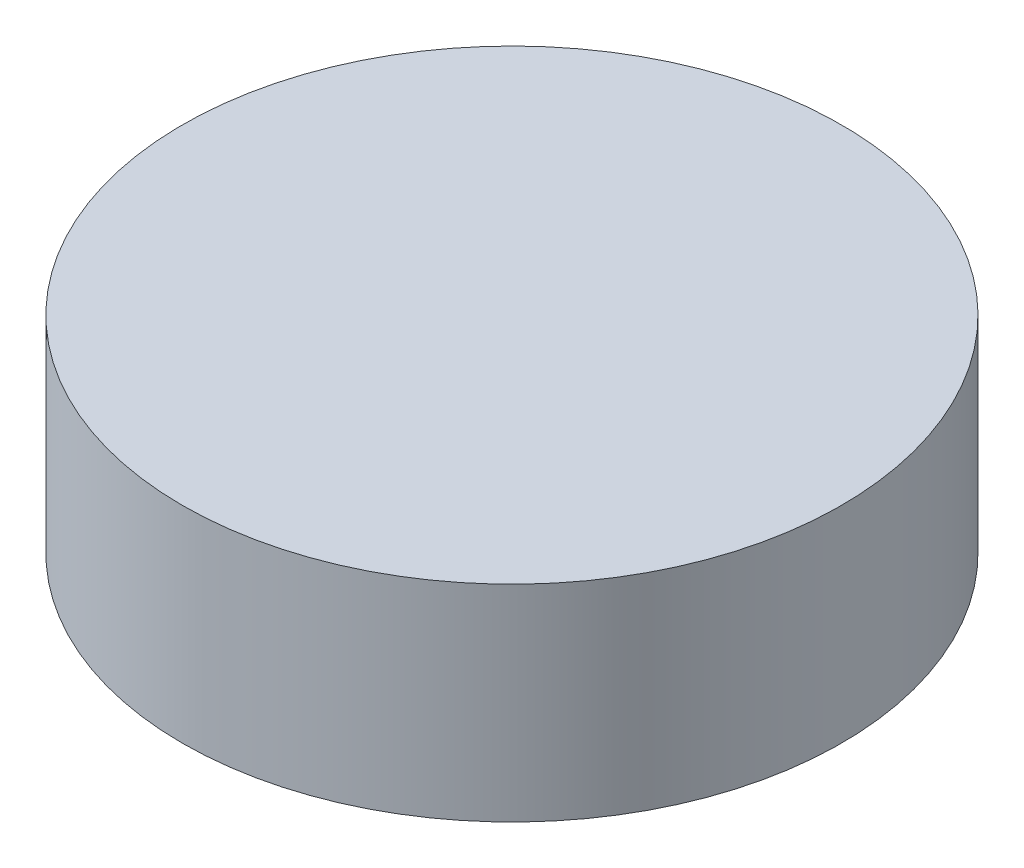
SolidWorks part; units mm, degrees
material "Polyethylene Cross-Linked"
ref_plane "Front Plane" through (0, 0, 0) normal (0, 0, 1) x (1, 0, 0)
ref_plane "Top Plane" through (0, 0, 0) normal (0, 1, 0) x (1, 0, 0)
ref_plane "Right Plane" through (0, 0, 0) normal (1, 0, 0) x (0, 0, -1)
sketch "Sketch2" plane through (0, 0, 0) normal (0, 1, 0) x (1, 0, 0)
  circle A0 centre (0, 0) radius 28.575
  dimension "D1" = 57.15
extrude "Boss-Extrude1" add sketch "Sketch2" along normal blind 17.8594
shell "Shell1" thickness 2.54
